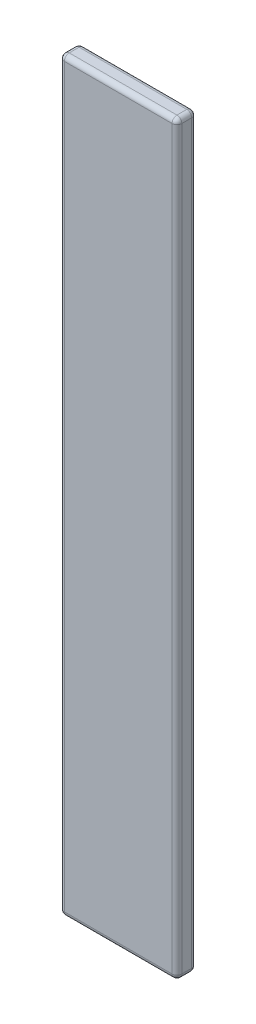
SolidWorks part; units mm, degrees
ref_plane "Front Plane" through (0, 0, 0) normal (0, 0, 1) x (1, 0, 0)
ref_plane "Top Plane" through (0, 0, 0) normal (0, 1, 0) x (1, 0, 0)
ref_plane "Right Plane" through (0, 0, 0) normal (1, 0, 0) x (0, 0, -1)
sketch "Sketch1" plane through (0, 0, 0) normal (0, 0, 1) x (1, 0, 0)
  line L1 (-24, -152.5) -> (24, -152.5)
  line L2 (-24, -152.5) -> (-24, 152.5)
  line L3 (-24, 152.5) -> (24, 152.5)
  line L4 (24, -152.5) -> (24, 152.5)
  line L5 (-24, -152.5) -> (24, 152.5) construction
  line L6 (-24, 152.5) -> (24, -152.5) construction
  point P0 (0, 0)
  dimension "D1" = 305
  dimension "D2" = 48
extrude "Boss-Extrude1" add sketch "Sketch1" along normal blind 8
fillet "Fillet1" radius 2 12 edges at (0, 152.5, 0) (-24, 0, 0) (0, -152.5, 0) (24, 0, 0) (0, -152.5, 8) (-24, 0, 8) (0, 152.5, 8) (24, 0, 8) (24, -152.5, 4) (-24, -152.5, 4) (-24, 152.5, 4) (24, 152.5, 4)
